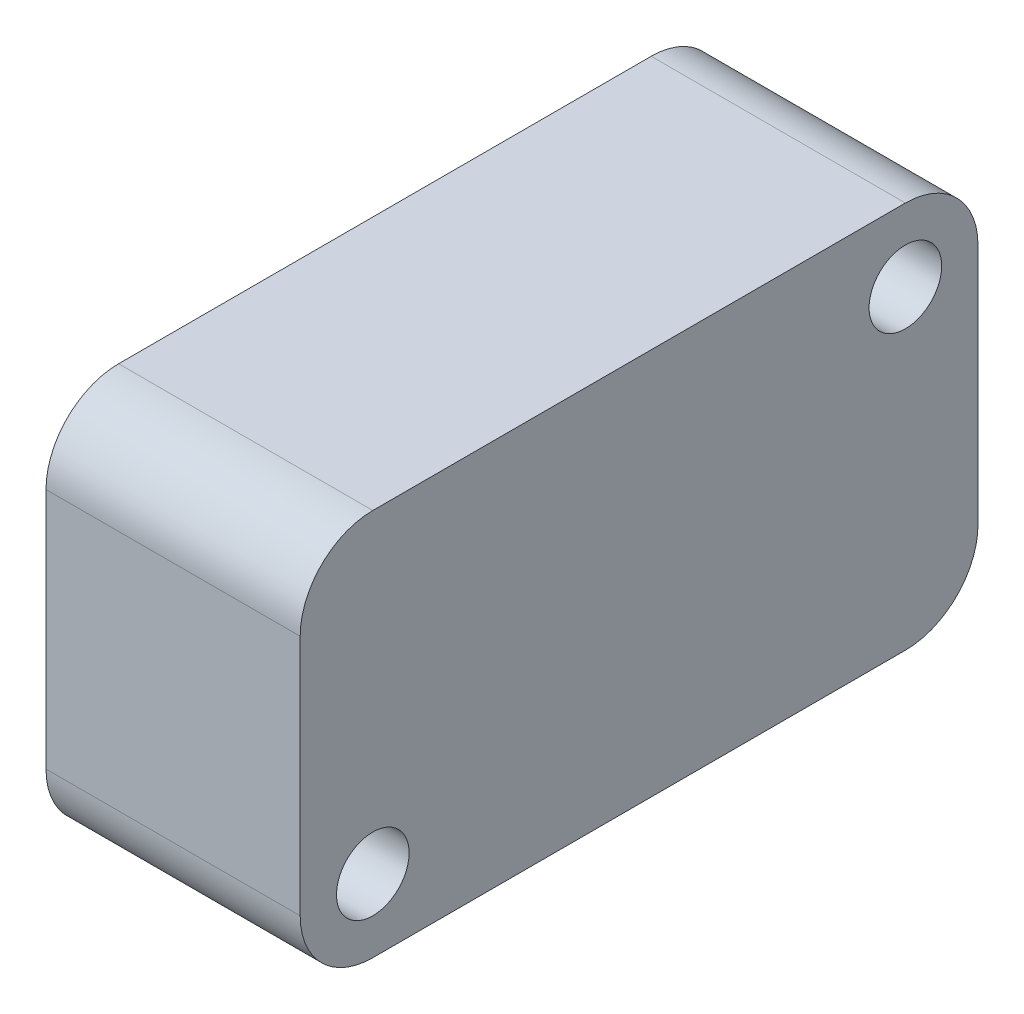
SolidWorks part; units mm, degrees
ref_plane "Front Plane" through (0, 0, 0) normal (0, 0, 1) x (1, 0, 0)
ref_plane "Top Plane" through (0, 0, 0) normal (0, 1, 0) x (1, 0, 0)
ref_plane "Right Plane" through (0, 0, 0) normal (1, 0, 0) x (0, 0, -1)
sketch "Sketch1" plane through (0, 0, 0) normal (1, 0, 0) x (0, 0, -1)
  line L1 (-14, 8) -> (14, 8)
  line L2 (-14, 8) -> (-14, -8)
  line L3 (-14, -8) -> (14, -8)
  line L4 (14, 8) -> (14, -8)
  line L5 (-14, 8) -> (14, -8) construction
  line L6 (-14, -8) -> (14, 8) construction
  point P0 (0, 0)
  dimension "D1" = 28
  dimension "D2" = 16
extrude "Boss-Extrude1" add sketch "Sketch1" along normal blind 10.5
sketch "Sketch2" plane through (10.5, 0, 0) normal (1, 0, 0) x (0, 0, -1)
  line L0 (-14, 8) -> (-14, -8) construction
  line L1 (-14, -8) -> (14, -8) construction
  line L2 (14, -8) -> (14, 8) construction
  line L3 (14, 8) -> (-14, 8) construction
  circle A0 centre (11, 5) radius 1.5
  circle A1 centre (-11, -5) radius 1.5
  dimension "D1" = 3
  dimension "D2" = 3
  dimension "D3" = 3
  dimension "D4" = 3
  dimension "D5" = 3
extrude "Cut-Extrude1" cut sketch "Sketch2" against normal through all
fillet "Fillet1" radius 3 4 edges at (5.25, -8, -14) (5.25, 8, -14) (5.25, 8, 14) (5.25, -8, 14)
sketch "Sketch3" plane through (0, -8, 0) normal (0, -1, 0) x (1, 0, 0)
  line L0 (0, -11) -> (10.5, -11) construction
  line L1 (3, -8) -> (7.5, -8)
  line L2 (3, -8) -> (3, -10.5)
  line L3 (3, -10.5) -> (7.5, -10.5)
  line L4 (7.5, -8) -> (7.5, -10.5)
  line L5 (10.5, -14) -> (0, -14) construction
  point P8 (5.25, -11)
  point P9 (5.25, -10.5)
  dimension "D1" = 3.5
  dimension "D2" = 2.5
  dimension "D3" = 4.5
extrude "Boss-Extrude2" add sketch "Sketch3" along normal blind 2.5
fillet "Fillet2" radius 0.5 2 edges at (5.25, -10.5, -10.5) (5.25, -10.5, -8)
